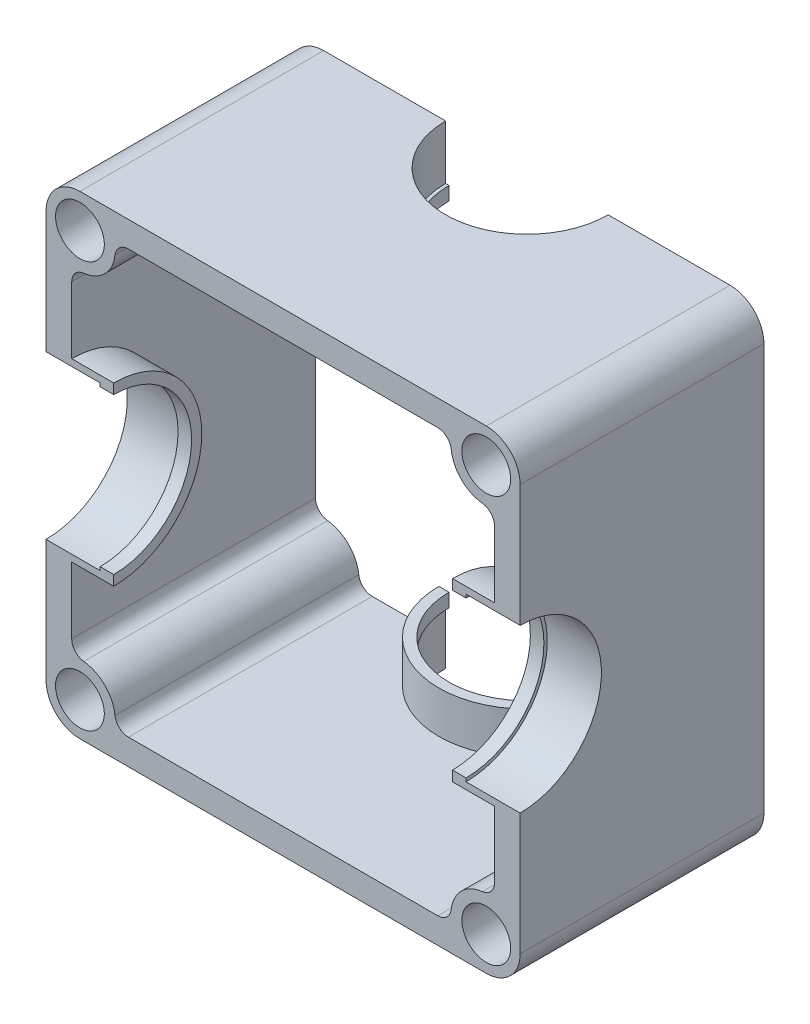
SolidWorks part; units mm, degrees
ref_plane "前视基准面" through (0, 0, 0) normal (0, 0, 1) x (1, 0, 0)
ref_plane "上视基准面" through (0, 0, 0) normal (0, 1, 0) x (1, 0, 0)
ref_plane "右视基准面" through (0, 0, 0) normal (1, 0, 0) x (0, 0, -1)
other "Configuration Table"
sketch "草图1" plane through (0, 0, 0) normal (0, 0, 1) x (-1, 0, 0)
  line L8 (-17.5, 15) -> (-17.5, -15)
  line L9 (-15, -17.5) -> (15, -17.5)
  line L10 (17.5, -15) -> (17.5, 15)
  line L11 (15, 17.5) -> (-15, 17.5)
  line L16 (15.6047, -11.417) -> (15.6047, 11.417)
  line L17 (-11.417, -15.6047) -> (11.417, -15.6047)
  line L18 (-15.6047, 11.417) -> (-15.6047, -11.417)
  line L19 (11.417, 15.6047) -> (-11.417, 15.6047)
  circle A2 centre (-15, -15) radius 1.8
  arc A8 (-15, 17.5) -> (-17.5, 15) centre (-15, 15) ccw
  arc A9 (-17.5, -15) -> (-15, -17.5) centre (-15, -15) ccw
  arc A10 (15, -17.5) -> (17.5, -15) centre (15, -15) ccw
  arc A11 (17.5, 15) -> (15, 17.5) centre (15, 15) ccw
  circle A12 centre (15, -15) radius 1.8
  circle A14 centre (15, 15) radius 1.8
  circle A16 centre (-15, 15) radius 1.8
  arc A38 (12.411, 14.7144) -> (14.7144, 12.411) centre (15, 15) ccw
  arc A39 (15.6047, 11.417) -> (14.7144, 12.411) centre (14.6048, 11.4171) ccw
  arc A40 (14.7144, -12.411) -> (15.6047, -11.417) centre (14.6048, -11.4171) ccw
  arc A41 (14.7144, -12.411) -> (12.411, -14.7144) centre (15, -15) ccw
  arc A42 (11.417, -15.6047) -> (12.411, -14.7144) centre (11.4171, -14.6048) ccw
  arc A43 (-12.411, -14.7144) -> (-11.417, -15.6047) centre (-11.4171, -14.6048) ccw
  arc A44 (-12.411, -14.7144) -> (-14.7144, -12.411) centre (-15, -15) ccw
  arc A45 (-15.6047, -11.417) -> (-14.7144, -12.411) centre (-14.6048, -11.4171) ccw
  arc A46 (-14.7144, 12.411) -> (-15.6047, 11.417) centre (-14.6048, 11.4171) ccw
  arc A47 (-14.7144, 12.411) -> (-12.411, 14.7144) centre (-15, 15) ccw
  arc A48 (-11.417, 15.6047) -> (-12.411, 14.7144) centre (-11.4171, 14.6048) ccw
  arc A49 (12.411, 14.7144) -> (11.417, 15.6047) centre (11.4171, 14.6048) ccw
extrude "凸台-拉伸1" add sketch "草图1" along normal blind 42
sketch "草图2" plane through (0, 17.5, 0) normal (0, 1, 0) x (1, 0, 0)
  line L0 (0, 0) -> (0, -12)
  circle A0 centre (0, -12) radius 6
  dimension "D2" = 12
  dimension "D1" = 12
extrude "切除-拉伸1" cut sketch "草图2" against normal through all
sketch "草图3" plane through (-17.5, 0, 0) normal (-1, 0, 0) x (0, 0, 1)
  line L0 (0, 0) -> (30, 0)
  circle A0 centre (30, 0) radius 6
  dimension "D2" = 12
  dimension "D1" = 30
extrude "切除-拉伸2" cut sketch "草图3" against normal through all
sketch "草图5" plane through (17.5, 0, 0) normal (1, 0, 0) x (0, 0, -1)
  line L0 (0, 0) -> (-12, 0)
  line L1 (-12, 0) -> (-12, -24.9743)
  line L3 (-30, 0) -> (-30, -24.9743)
  line L5 (-30, 0) -> (-30, 23.8795)
  line L7 (-12, 23.8795) -> (-12, 0)
  line L8 (-12, -24.9743) -> (12.1166, -24.9743)
  line L9 (12.1166, -24.9743) -> (12.1166, 23.8795)
  line L10 (12.1166, 23.8795) -> (-12, 23.8795)
  line L11 (-30, -24.9743) -> (-47.4121, -24.9743)
  line L12 (-47.4121, -24.9743) -> (-47.4121, 25.2382)
  line L13 (-47.4121, 25.2382) -> (-30, 23.8795)
  circle M15 centre (-30, 0) radius 6
  line M16 (0, -15) -> (0, 15)
  line M17 (0, 15) -> (-42, 15)
  line M18 (-42, 15) -> (-42, -15)
  line M19 (-42, -15) -> (0, -15)
  dimension "D1" = 12
extrude "切除-拉伸3" cut sketch "草图5" against normal through all contours L13 L12 L11 L3 L5 M19 M18 M17 | L5 L3 M15 M17 M18 M19 | L7 L0 M17 M16 | L9 L10 L7 L1 L8 M17 M16 M19 | L0 L1 M19 M16
sketch "草图6" plane through (0, 15.6047, 0) normal (0, -1, 0) x (-1, 0, 0)
  line L0 (-6, -12) -> (-6.5, -12)
  line L1 (6, -12) -> (6.5, -12)
  arc A0 (-6, -12) -> (6, -12) centre (0, -12) ccw
  arc A1 (-6.5, -12) -> (6.5, -12) centre (0, -12) ccw
  dimension "D1" = 12
  dimension "D2" = 13
extrude "凸台-拉伸2" add sketch "草图6" along normal blind 2.1
sketch "草图7" plane through (0, 13.5047, 0) normal (0, -1, 0) x (-1, 0, 0)
  line L0 (-6.5, -12) -> (-5.75, -12)
  line L1 (5.75, -12) -> (6.5, -12)
  arc A0 (-6.5, -12) -> (6.5, -12) centre (0, -12) ccw
  arc A1 (-5.75, -12) -> (5.75, -12) centre (0, -12) ccw
  dimension "D1" = 13
  dimension "D2" = 11.5
extrude "凸台-拉伸3" add sketch "草图7" along normal blind 1
ref_plane "基准面1" through (0, 0, 0) normal (0, -1, 0) x (-1, 0, 0)
mirror "镜向1" about plane through (0, 0, 0) normal (0, -1, 0) of "凸台-拉伸2", "凸台-拉伸3"
sketch "草图8" plane through (15.6047, 0, 0) normal (-1, 0, 0) x (0, 0, 1)
  line L0 (30, -6.5) -> (30, -6)
  line L2 (30, 6) -> (30, 6.5)
  arc A0 (30, 6) -> (30, -6) centre (30, 0) ccw
  arc A1 (30, 6.5) -> (30, -6.5) centre (30, 0) ccw
  dimension "D2" = 13
extrude "凸台-拉伸4" add sketch "草图8" along normal blind 2.1
sketch "草图9" plane through (13.5047, 0, 0) normal (-1, 0, 0) x (0, 0, 1)
  line L0 (30, -6.5) -> (30, -5.75)
  line L2 (30, 5.75) -> (30, 6.5)
  arc A0 (30, 6.5) -> (30, -6.5) centre (30, 0) ccw
  arc A1 (30, 5.75) -> (30, -5.75) centre (30, 0) ccw
  dimension "D1" = 13
  dimension "D2" = 11.5
extrude "凸台-拉伸5" add sketch "草图9" along normal blind 1
ref_plane "基准面2" through (0, 0, 0) normal (-1, 0, 0) x (0, 0, 1)
mirror "镜向2" about plane through (0, 0, 0) normal (-1, 0, 0) of "凸台-拉伸4", "凸台-拉伸5"
